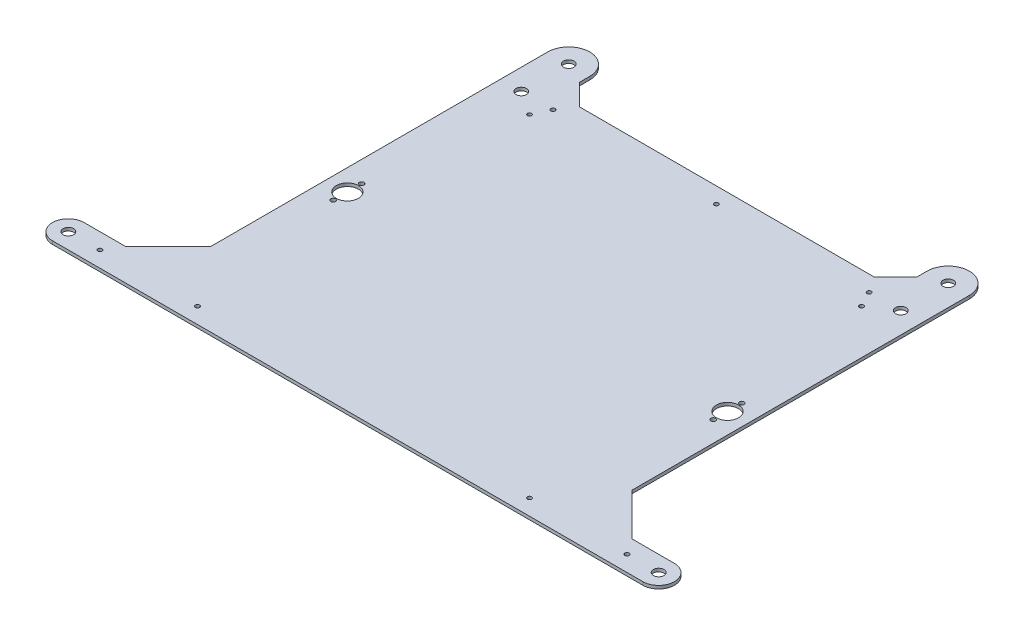
SolidWorks part; units mm, degrees
ref_plane "Front Plane" through (0, 0, 0) normal (0, 0, 1) x (1, 0, 0)
ref_plane "Top Plane" through (0, 0, 0) normal (0, 1, 0) x (1, 0, 0)
ref_plane "Right Plane" through (0, 0, 0) normal (1, 0, 0) x (0, 0, -1)
sketch "Sketch1" plane through (0, 0, 0) normal (0, 1, 0) x (1, 0, 0)
  line L0 (0, 0) -> (0, -157.5) construction
  line L1 (0, -157.5) -> (-280, -157.5) construction
  line L2 (0, -157.5) -> (280, -157.5) construction
  line L3 (-200.2852, -142.5) -> (199.7148, -142.5) construction
  line L4 (-200.2852, -142.5) -> (-280, -142.5)
  line L5 (-157.5, 157.5) -> (157.5, -157.5) construction
  line L6 (-157.5, -157.5) -> (157.5, 157.5) construction
  line L7 (-200.2852, -142.5) -> (-200.2852, 187.5)
  line L8 (-160.2852, 187.5) -> (199.7148, 187.5)
  line L9 (199.7148, 187.5) -> (199.7148, -142.5)
  line L10 (-280, -172.5) -> (280, -172.5)
  line L11 (-180.2852, 172.5) -> (-180.2852, -157.5) construction
  line L12 (280, -142.5) -> (199.7148, -142.5)
  line L13 (-200.2852, 187.5) -> (-200.2852, 217.5)
  line L15 (-160.2852, 217.5) -> (-160.2852, 187.5)
  circle A0 centre (-157.5, 157.5) radius 2
  circle A1 centre (157.5, 157.5) radius 2
  circle A2 centre (157.5, -157.5) radius 2
  circle A3 centre (-157.5, -157.5) radius 2
  circle A4 centre (-280, -157.5) radius 5
  circle A5 centre (280, -157.5) radius 5
  arc A6 (-280, -142.5) -> (-280, -172.5) centre (-280, -157.5) ccw
  arc A7 (280, -172.5) -> (280, -142.5) centre (280, -157.5) ccw
  circle A8 centre (-250, -157.5) radius 2
  circle A9 centre (250, -157.5) radius 2
  circle A10 centre (-180.2852, 172.5) radius 5
  circle A11 centre (179.7148, 172.5) radius 5
  circle A12 centre (-150.2852, 172.5) radius 2
  circle A13 centre (4.7148, 172.5) radius 2
  circle A14 centre (149.7148, 172.5) radius 2
  circle A15 centre (-180.2852, 7.5) radius 10.5
  circle A16 centre (-180.2852, 21) radius 2.25
  circle A17 centre (-180.2852, -6) radius 2.25
  circle A18 centre (180.2852, -6) radius 2.25
  circle A19 centre (180.2852, 21) radius 2.25
  circle A20 centre (180.2852, 7.5) radius 10.5
  circle A21 centre (-180.2852, 217.5) radius 5
  arc A22 (-200.2852, 217.5) -> (-160.2852, 217.5) centre (-180.2852, 217.5) cw
  point P0 (0, 0)
  dimension "D3" = 445.4773
  dimension "D2" = 4
  dimension "D6" = 10
  dimension "D8" = 30
  dimension "D18" = 21
  dimension "D21" = 4.5
  dimension "D1" = 315
  dimension "D4" = 445.4773
  dimension "D9" = 30
  dimension "D10" = 400
  dimension "D11" = 20
  dimension "D12" = 15
  dimension "D13" = 15
  dimension "D14" = 20
  dimension "D15" = 30
  dimension "D16" = 30
  dimension "D17" = 330
  dimension "D19" = 27
  dimension "D20" = 13.5
  dimension "D23" = 280
extrude "Boss-Extrude1" add sketch "Sketch1" along normal blind 3
sketch "Sketch2" plane through (0, 3, 0) normal (0, 1, 0) x (1, 0, 0)
  line L0 (199.7148, 187.5) -> (199.7148, 217.5)
  line L1 (159.7148, 217.5) -> (159.7148, 187.5)
  line L2 (199.7148, 187.5) -> (-160.2852, 187.5) construction
  line L3 (199.7148, 187.5) -> (159.7148, 187.5)
  arc A0 (199.7148, 217.5) -> (159.7148, 217.5) centre (179.7148, 217.5) ccw
  circle A1 centre (179.7148, 217.5) radius 5
  circle A2 centre (179.7148, 172.5) radius 5 construction
  dimension "D1" = 20
  dimension "D2" = 0
extrude "Boss-Extrude2" add sketch "Sketch2" against normal up to surface (3 mm away) up to face at (-32.1711, 0, 8.5)
chamfer "Chamfer2" distance 20 angle 45 2 edges at (-160.2852, 1.5, -187.5) (159.7148, 1.5, -187.5)
chamfer "Chamfer3" distance 40 angle 45 2 edges at (199.7148, 1.5, 142.5) (-200.2852, 1.5, 142.5)
